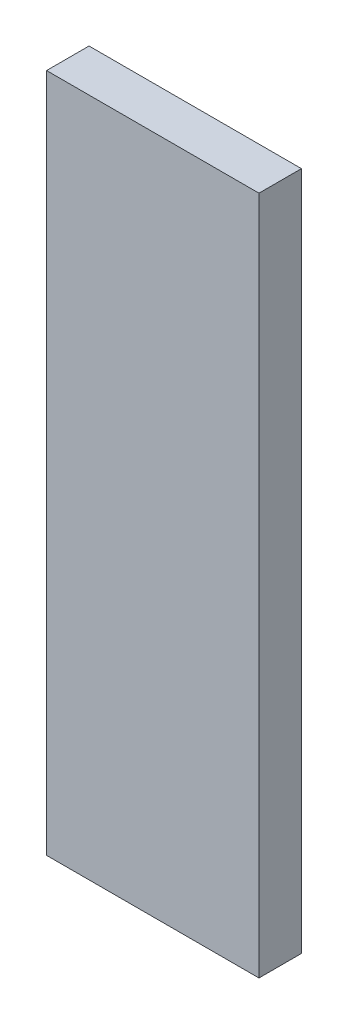
SolidWorks part; units mm, degrees
ref_plane "前视基准面" through (0, 0, 0) normal (0, 0, 1) x (1, 0, 0)
ref_plane "上视基准面" through (0, 0, 0) normal (0, 1, 0) x (1, 0, 0)
ref_plane "右视基准面" through (0, 0, 0) normal (1, 0, 0) x (0, 0, -1)
other "Configuration Table"
sketch "草图1" plane through (0, 0, 0) normal (0, 0, 1) x (1, 0, 0)
  line L1 (-25, -80) -> (25, -80)
  line L2 (-25, -80) -> (-25, 80)
  line L3 (-25, 80) -> (25, 80)
  line L4 (25, -80) -> (25, 80)
  line L5 (-25, -80) -> (25, 80) construction
  line L6 (-25, 80) -> (25, -80) construction
  point P0 (0, 0)
  dimension "D1" = 50
  dimension "D2" = 160
extrude "凸台-拉伸1" add sketch "草图1" along normal mid plane 10
